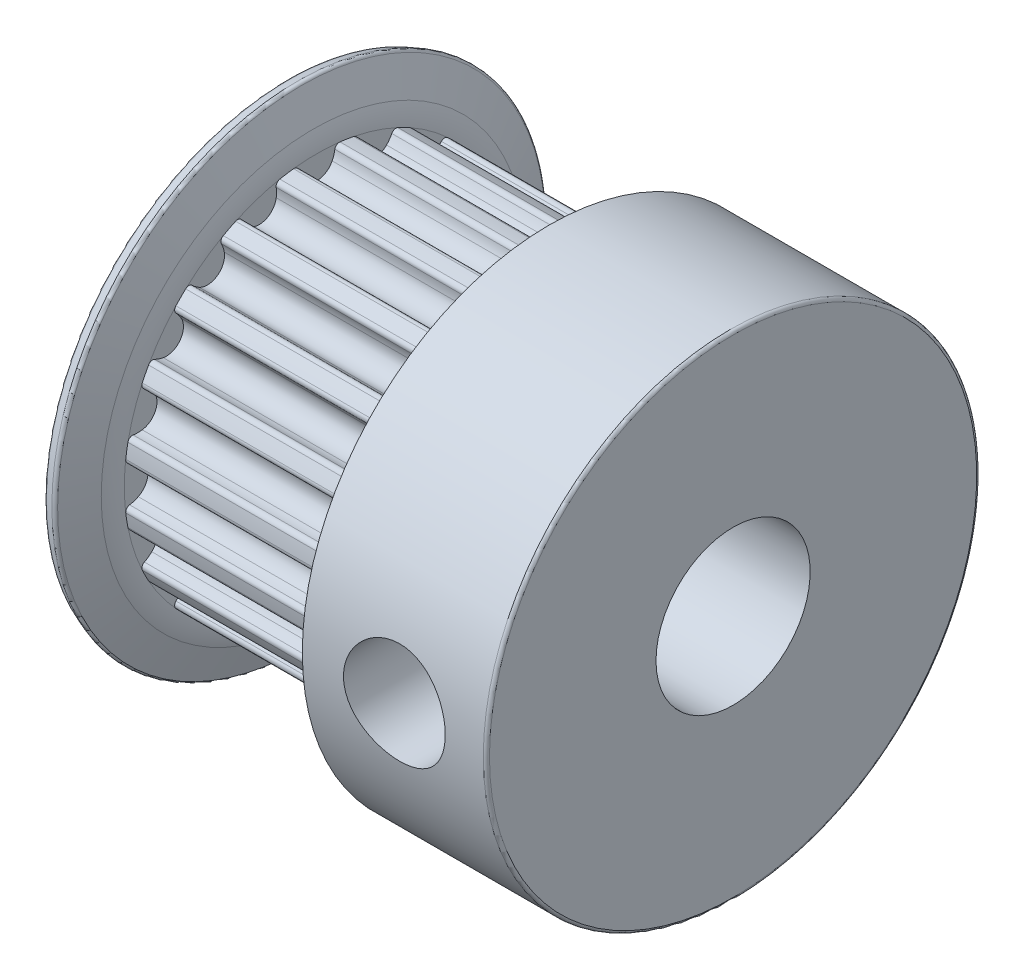
SolidWorks part; units mm, degrees
ref_plane "Front" through (0, 0, 0) normal (0, 0, 1) x (1, 0, 0)
ref_plane "Top" through (0, 0, 0) normal (0, 1, 0) x (1, 0, 0)
ref_plane "Right" through (0, 0, 0) normal (1, 0, 0) x (0, 0, -1)
sketch "Sketch1" plane through (0, 0, 0) normal (1, 0, 0) x (0, 0, -1)
  circle A0 centre (0, 0) radius 2.5
  circle A1 centre (0, 0) radius 6.2392
  dimension "D1" = 5
  dimension "D2" = 12.4784
extrude "Boss-Extrude1" add sketch "Sketch1" along normal mid plane 7
sketch "Sketch2" plane through (0, 0, 0) normal (1, 0, 0) x (0, 0, -1)
  line L0 (0, 0) -> (0, 6.2392) construction
  circle A0 centre (0, 0) radius 6.2392 construction
  arc A1 (0.7537, 6.1935) -> (-0.7537, 6.1935) centre (0, 0) ccw
  arc A2 (-0.7537, 6.1935) -> (-0.5874, 6.0683) centre (-0.7355, 6.0446) cw
  arc A3 (-0.5874, 6.0683) -> (-0.4989, 5.7882) centre (0.4, 6.2264) ccw
  arc A4 (-0.4989, 5.7882) -> (0.4989, 5.7882) centre (0, 6.0314) ccw
  arc A5 (0.7537, 6.1935) -> (0.5874, 6.0683) centre (0.7355, 6.0446) ccw
  arc A6 (0.5874, 6.0683) -> (0.4989, 5.7882) centre (-0.4, 6.2264) cw
  dimension "D1" = 0.15
  dimension "D2" = 1
  dimension "D3" = 0.555
  dimension "D4" = 0.4
extrude "Cut-Extrude1" cut sketch "Sketch2" against normal mid plane 7
pattern_circular "CirPattern1" count 20 over 360 about axis through (0, 0, 0) along (1, 0, 0) of "Cut-Extrude1"
sketch "Sketch3" plane through (0, 0, 0) normal (0, 0, 1) x (1, 0, 0)
  line L0 (0, 6.2392) -> (0, 0) construction
  line L1 (0, 0) -> (5.1043, 0) construction
  line L2 (-3.5, 2.5) -> (-3.5, 6.2392)
  line L3 (-3.614, 6.8748) -> (-4.0312, 8)
  line L4 (-4.0312, 8) -> (-4.5, 7.8262)
  line L5 (-4.5, 7.8262) -> (-4.0829, 6.701)
  line L7 (-4, 6.2392) -> (-4, 5)
  line L8 (-4, 5) -> (-4.25, 5)
  line L9 (-4.25, 5) -> (-4.25, 4.5)
  line L10 (-4.25, 4.5) -> (-4.5, 4.5)
  line L11 (-4.5, 4.5) -> (-4.5, 2.5)
  line L12 (-4.5, 2.5) -> (-3.5, 2.5)
  line L16 (4.5, 4.5) -> (4.5, 2.5)
  line L17 (4.25, 4.5) -> (4.5, 4.5)
  line L18 (4.25, 5) -> (4.25, 4.5)
  line L19 (4, 5) -> (4.25, 5)
  line L20 (4, 6.2392) -> (4, 5)
  line L21 (4.5, 7.8262) -> (4.0829, 6.701)
  line L22 (4.0312, 8) -> (4.5, 7.8262)
  line L23 (3.614, 6.8748) -> (4.0312, 8)
  line L24 (3.5, 2.5) -> (3.5, 6.2392)
  line L25 (4.5, 2.5) -> (3.5, 2.5)
  arc A0 (-3.5, 6.2392) -> (-3.614, 6.8748) centre (-5.3285, 6.2392) ccw
  arc A1 (-4.0829, 6.701) -> (-4, 6.2392) centre (-5.3285, 6.2392) cw
  arc A2 (4.0829, 6.701) -> (4, 6.2392) centre (5.3285, 6.2392) ccw
  arc A3 (3.5, 6.2392) -> (3.614, 6.8748) centre (5.3285, 6.2392) cw
  dimension "D1" = 9
  dimension "D2" = 16
  dimension "D3" = 0.5
  dimension "D4" = 1.2
  dimension "D5" = 1
  dimension "D6" = 10
revolve "Revolve1" add sketch "Sketch3" angle 360 about L1
sketch "Sketch4" plane through (0, 0, 0) normal (0, 0, 1) x (1, 0, 0)
  line L0 (0, 7.2927) -> (0, 0) construction
  line L1 (0, 0) -> (12.9063, 0) construction
  line L2 (4.0312, 8) -> (4.0312, 0) construction
  line L4 (0, 0) -> (5.1043, 0) construction
  line L5 (4.0312, 8) -> (10, 8)
  line L6 (10, 8) -> (10, 2.5)
  line L7 (10, 2.5) -> (3.7429, 2.5)
  line L8 (3.7429, 2.5) -> (4.0312, 8)
  line L9 (4.5, 2.5) -> (3.5, 2.5) construction
  line L10 (-4.5, 4.5) -> (-4.5, 2.5) construction
  dimension "D1" = 16
  dimension "D2" = 14.5
  dimension "D3" = 93
revolve "Revolve2" add sketch "Sketch4" angle 360 about L1
fillet "Fillet1" radius 0.1 6 edges at (-4, 0, 5) (-4.25, 0, 5) (-4.25, 0, 4.5) (10, 0, 8) (-4.0312, 0, 8) (-4.5, 0, 7.8262)
sketch "Sketch5" plane through (0, 0, 0) normal (0, 0, 1) x (1, 0, 0)
  line L0 (4.0312, 0) -> (10, 0) construction
  line L1 (4.0312, 8) -> (4.0312, 0) construction
  line L2 (10, 8) -> (10, 2.5) construction
hole_wizard "M4 Tapped Hole1" positions "Sketch7" profile "Sketch6" tap size "M4" standard "ISO"
sketch "Sketch7" plane through (0, 0, 0) normal (0, 0, 1) x (1, 0, 0)
  line L0 (4.0312, 0) -> (10, 0) construction
  point P0 (7.0156, 0)
sketch "Sketch6" plane through (7.0156, 0, 0) normal (1, 0, 0) x (0, 1, 0)
  line L0 (0, 0) -> (0, 8)
  line L1 (0, 8) -> (1.65, 8)
  line L2 (1.65, 8) -> (1.65, 0)
  line L5 (1.65, 0) -> (0, 0)
  line L11 (0, -6.35) -> (0, 107.95) construction
  dimension "Thru Tap Drill Dia." = 3.3
  dimension "Thru Tap Drill Depth" = 8
cosmetic thread "Hole Thread1" parameters "D2"=4
equation "\"Pitch\"= 2"
equation "\"Outside Fillet\"= .15"
equation "\"Side Radius\"= 1"
equation "\"Bottom Radius\"= .555"
equation "\"Tooth height\"= .75"
equation "\"Teeth_Count\"=20"
equation "\"Side radius offset\"= .4"
equation "\"Effective radius offset\"= 0.254"
equation "\"Belt width\"= 6"
equation "\"Pulley extra width\"= 1"
equation "\"Rim_Diameter\"=16"
equation "\"Rim_Width\"= 1"
equation "\"Pulley_Width\"= \"Belt width\" + \"Pulley extra width\" + 2 * \"Rim_Width\""
equation "\"Overall Width\"=14.5"
equation "\"Fastening Diameter\"=16"
equation "\"D2@Sketch1\"=\"Pitch\"*\"Teeth_Count\"/pi - \"Effective radius offset\""
equation "\"D1@Boss-Extrude1\"=\"Belt width\"+\"Pulley extra width\""
equation "\"D1@Sketch2\"=\"Outside Fillet\""
equation "\"D2@Sketch2\"=\"Side Radius\""
equation "\"D3@Sketch2\"=\"Bottom Radius\""
equation "\"D4@Sketch2\"=\"Side radius offset\""
equation "\"D1@Cut-Extrude1\"=\"Belt width\"+\"Pulley extra width\""
equation "\"D1@CirPattern1\"=\"Teeth_Count\""
equation "\"D2@Sketch3\"=\"Rim_Diameter\""
equation "\"D1@Sketch4\"=\"Fastening Diameter\""
equation "\"D2@Sketch4\"=\"Overall Width\""
